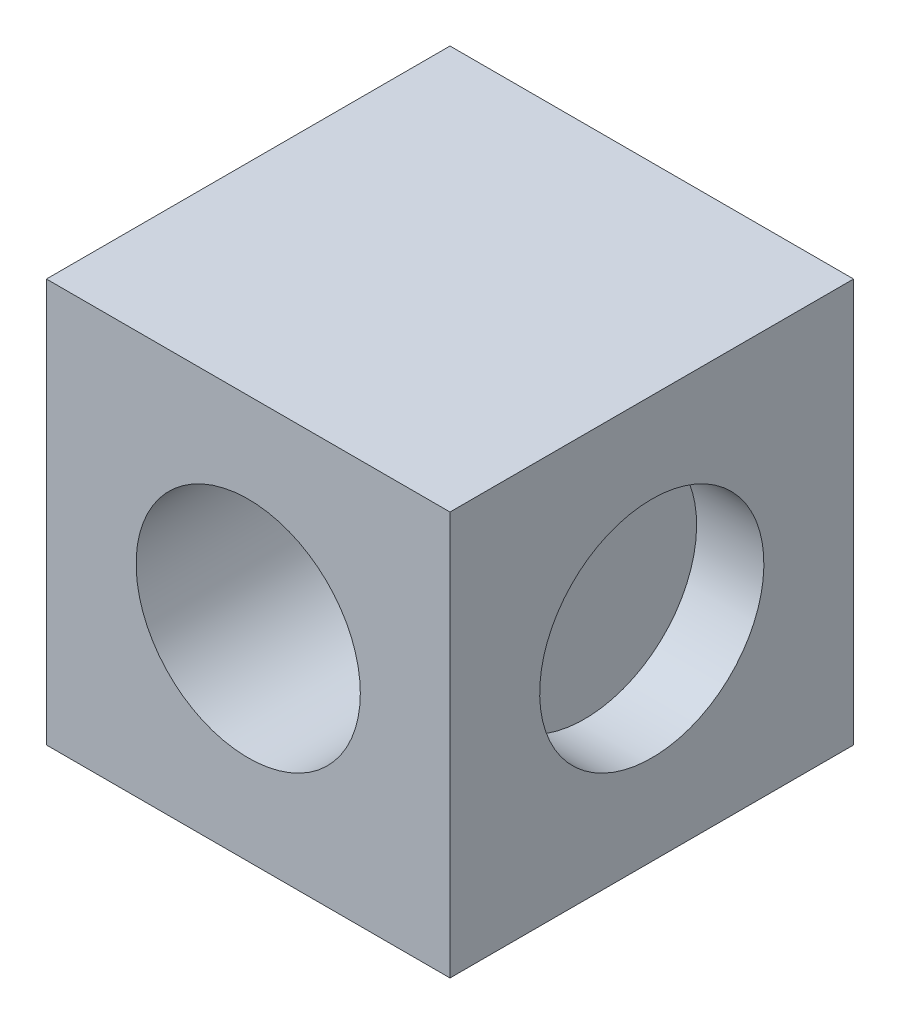
SolidWorks part; units mm, degrees
ref_plane "Front Plane" through (0, 0, 0) normal (0, 0, 1) x (1, 0, 0)
ref_plane "Top Plane" through (0, 0, 0) normal (0, 1, 0) x (1, 0, 0)
ref_plane "Right Plane" through (0, 0, 0) normal (1, 0, 0) x (0, 0, -1)
sketch "Sketch1" plane through (0, 0, 0) normal (0, 0, 1) x (1, 0, 0)
  line L1 (-9, 9) -> (9, 9)
  line L2 (-9, 9) -> (-9, -9)
  line L3 (-9, -9) -> (9, -9)
  line L4 (9, 9) -> (9, -9)
  line L5 (-9, 9) -> (9, -9) construction
  line L6 (-9, -9) -> (9, 9) construction
  circle A0 centre (0, 0) radius 5
  point P0 (0, 0)
  dimension "D3" = 10
  dimension "D1" = 18
  dimension "D2" = 18
extrude "Boss-Extrude1" add sketch "Sketch1" along normal blind 18
sketch "Sketch2" plane through (9, 0, 0) normal (1, 0, 0) x (0, 0, -1)
  line L0 (-18, -9) -> (0, -9) construction
  circle A0 centre (-9, 0) radius 5
  point P2 (0, 0)
  point P5 (-9, -9)
  point P6 (-9, 1.7934)
  point P7 (0, 0)
  dimension "D1" = 10
extrude "Cut-Extrude1" cut sketch "Sketch2" against normal blind 3
mirror "Mirror1" about plane through (0, 0, 0) normal (1, 0, 0) of "Cut-Extrude1"
